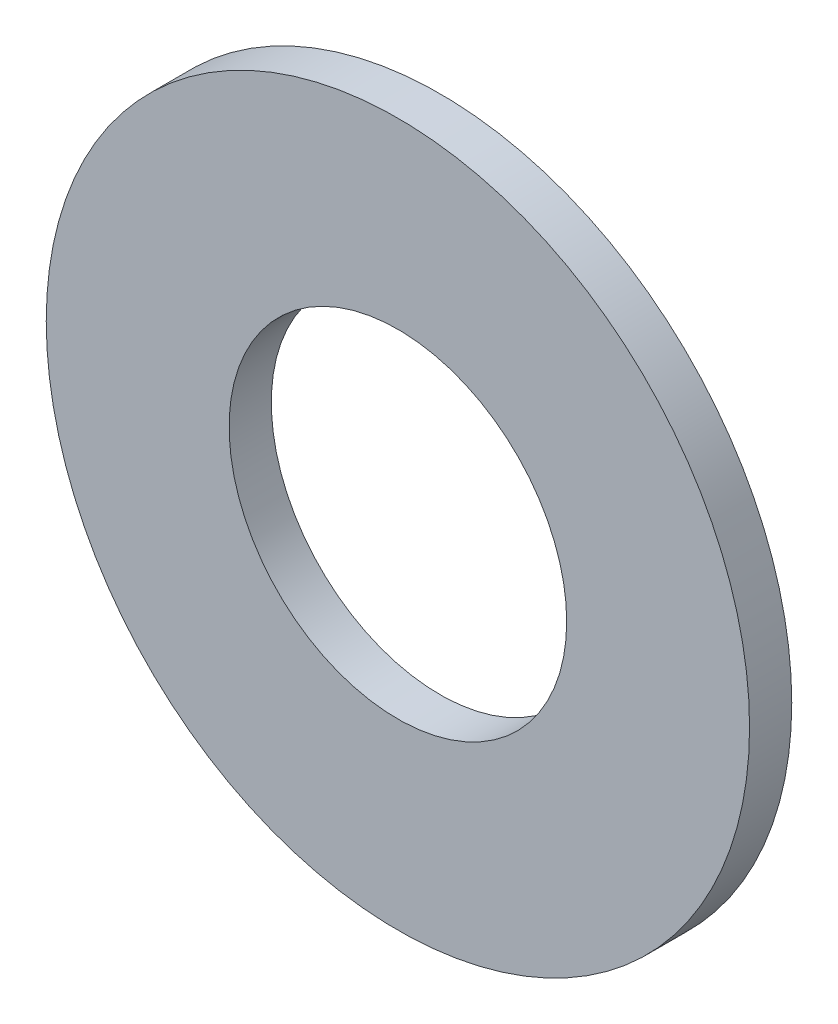
SolidWorks part; units mm, degrees
ref_plane "Plane1" through (0, 0, 0) normal (0, 0, 1) x (1, 0, 0)
ref_plane "Plane2" through (0, 0, 0) normal (0, 1, 0) x (1, 0, 0)
ref_plane "Plane3" through (0, 0, 0) normal (1, 0, 0) x (0, 0, -1)
extrude "Основание-Вытянуть" add sketch "Эскиз1" along normal blind 0.3
sketch "Эскиз1" plane through (0, 0, 0) normal (0, 0, 1) x (1, 0, 0)
  circle A0 centre (0, 0) radius 2.5
  circle A1 centre (0, 0) radius 1.2
  dimension "DН" = 5
  dimension "DВ" = 2.4
